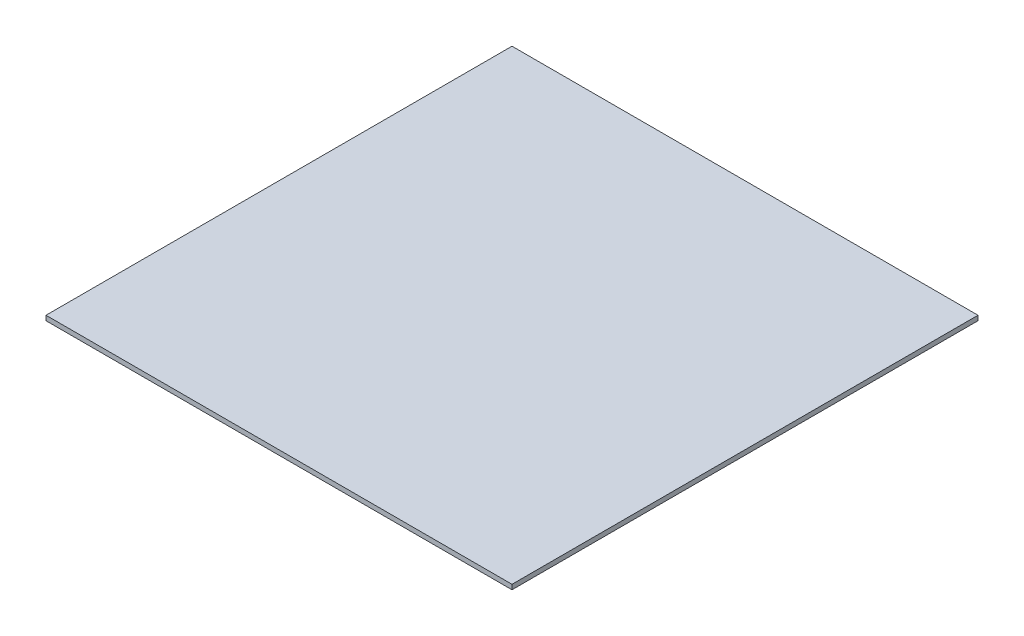
SolidWorks part; units mm, degrees
material "6061 Alloy"
ref_plane "Front Plane" through (0, 0, 0) normal (0, 0, 1) x (1, 0, 0)
ref_plane "Top Plane" through (0, 0, 0) normal (0, 1, 0) x (1, 0, 0)
ref_plane "Right Plane" through (0, 0, 0) normal (1, 0, 0) x (0, 0, -1)
sketch "Sketch1" plane through (0, 0, 0) normal (0, 1, 0) x (1, 0, 0)
  line L1 (195, -195) -> (-195, -195)
  line L2 (195, -195) -> (195, 195)
  line L3 (195, 195) -> (-195, 195)
  line L4 (-195, -195) -> (-195, 195)
  line L5 (195, -195) -> (-195, 195) construction
  line L6 (195, 195) -> (-195, -195) construction
  point P0 (0, 0)
  point P1 (0, 0)
  dimension "D1" = 390
extrude "Boss-Extrude1" add sketch "Sketch1" along normal blind 4
